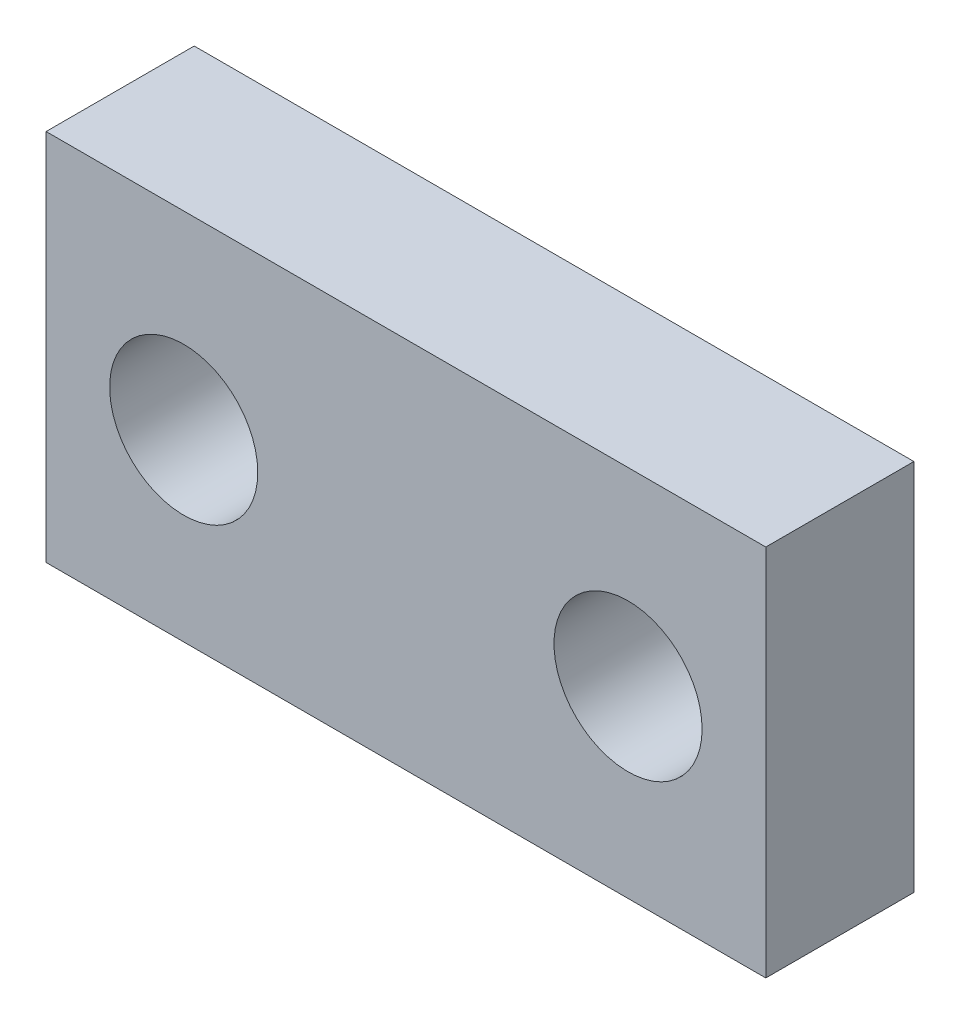
SolidWorks part; units mm, degrees
ref_plane "Plan de face" through (0, 0, 0) normal (0, 0, 1) x (1, 0, 0)
ref_plane "Plan de dessus" through (0, 0, 0) normal (0, 1, 0) x (1, 0, 0)
ref_plane "Plan de droite" through (0, 0, 0) normal (1, 0, 0) x (0, 0, -1)
sketch "Esquisse1" plane through (0, 0, 0) normal (0, 0, 1) x (1, 0, 0)
  line L0 (1.1946, 1.1272) -> (25.4899, 1.1272)
  line L1 (1.1946, 1.1272) -> (1.1946, -11.4728)
  line L2 (1.1946, -11.4728) -> (25.4899, -11.4728)
  line L3 (25.4899, 1.1272) -> (25.4899, -11.4728)
  circle A0 centre (20.8399, -5.2696) radius 2.5
  circle A1 centre (5.8399, -5.2696) radius 2.5
  dimension "D1" = 4.65
  dimension "D2" = 4.6452
  dimension "D3" = 15
extrude "Boss.-Extru.1" add sketch "Esquisse1" along normal blind 5
